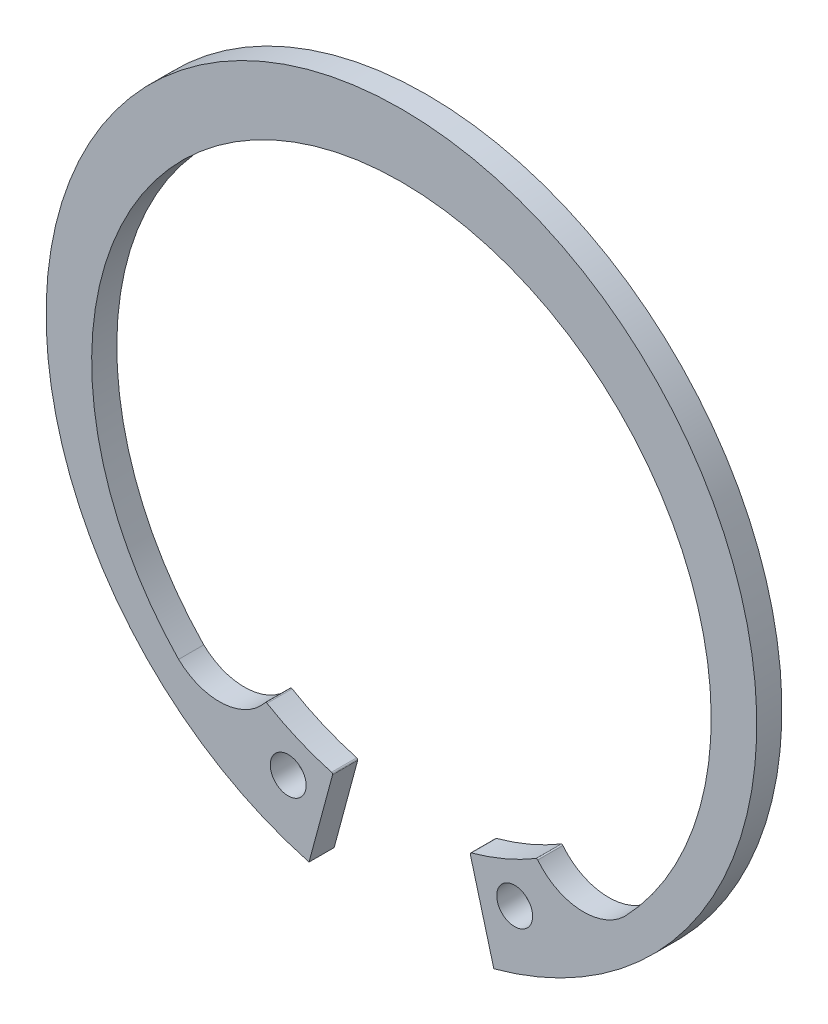
SolidWorks part; units mm, degrees
ref_plane "Plane1" through (0, 0, 0) normal (0, 0, 1) x (1, 0, 0)
ref_plane "Plane2" through (0, 0, 0) normal (0, 1, 0) x (1, 0, 0)
ref_plane "Plane3" through (0, 0, 0) normal (1, 0, 0) x (0, 0, -1)
sketch "Clipboard" plane through (0, 0, 0) normal (0, 0, 1) x (1, 0, 0)
  line L0 (0, 0) -> (4.4, 0)
  line L1 (0, 0) -> (0, 2.2)
  line L2 (0, 0) -> (0, -6.4)
  circle A0 centre (0, 0) radius 1.25
  circle A1 centre (0, 0) radius 23.5
  dimension "HoleDia" = 2.5
  dimension "BoreDia" = 47
  dimension "LargeSection" = 4.4
  dimension "SmallSection" = 2.2
  dimension "LugSection" = 6.4
sketch "BodySke" plane through (0, 0, 0) normal (0, 0, 1) x (1, 0, 0)
  line L0 (-1.5431, 0) -> (1.5431, 0) construction
  line L1 (0, 0) -> (0, 20.35) construction
  line L2 (6.4361, -23.8985) -> (5.4001, -20.0515)
  line L3 (-6.4361, -23.8985) -> (-5.4001, -20.0515)
  line L4 (0, 0) -> (14.6742, -19.9307) construction
  line L5 (0, 0) -> (-14.6742, -19.9307) construction
  line L6 (-7.5614, -18.1749) -> (-8.2115, -20.5889) construction
  line L7 (7.6913, -18.6572) -> (8.0817, -20.1067) construction
  arc A0 (-5.4001, -20.0515) -> (-9.8643, -17.733) centre (-7.8865, -19.3819) ccw
  arc A1 (9.8643, -17.733) -> (5.4001, -20.0515) centre (7.8865, -19.3819) ccw
  arc A2 (13.3698, -18.159) -> (-13.3698, -18.159) centre (0, -1.2254) ccw construction
  arc A3 (6.4361, -23.8985) -> (-6.4361, -23.8985) centre (0, 0) ccw
  circle A4 centre (7.8865, -19.3819) radius 1.25
  circle A5 centre (-7.8865, -19.3819) radius 1.25
  circle A6 centre (7.8865, -19.3819) radius 2.575 construction
  arc A7 (13.447, -18.0978) -> (-13.447, -18.0978) centre (0, -1.2254) ccw
  arc A8 (-7.8865, -19.3819) -> (7.8865, -19.3819) centre (0, 0) ccw construction
  arc A9 (-13.447, -18.0978) -> (-9.8643, -17.733) centre (-11.8421, -16.0841) ccw
  arc A10 (9.8643, -17.733) -> (13.447, -18.0978) centre (11.8421, -16.0841) ccw
  dimension "HoleDia" = 2.5
  dimension "HoleOffsetRad" = 20.925
  dimension "GrooveDia" = 49.5
  dimension "TipRad" = 2.575
  dimension "FilletRad" = 2.575
  dimension "LargeRad" = 20.35
  dimension "SmallRad" = 22.55
  dimension "SmallAngle" = 72.726
  dimension "GapAngle" = 30.145
extrude "Body" add sketch "BodySke" against normal blind 1.75
sketch "ModLugSke" plane through (0, 0, 0) normal (0, 0, 1) x (1, 0, 0)
  line L0 (6.4361, -23.8985) -> (4.7978, -17.815)
  line L1 (-6.4361, -23.8985) -> (-4.7978, -17.815)
  line L2 (12.689, -13.2556) -> (17.1146, -17.8788) construction
  line L3 (-12.689, -13.2556) -> (-17.1146, -17.8788) construction
  line L4 (-6.4361, -23.8985) -> (-5.4001, -20.0515) construction
  line L5 (5.4001, -20.0515) -> (6.4361, -23.8985) construction
  line L6 (0, 0) -> (0, -18.0732) construction
  line L7 (15.5173, -16.2102) -> (17.1146, -17.8788)
  line L8 (-17.1146, -17.8788) -> (-15.5173, -16.2102)
  arc A0 (6.4361, -23.8985) -> (17.1146, -17.8788) centre (0, 0) ccw
  arc A1 (-9.362, -15.7821) -> (-4.8678, -17.6926) centre (0, 0) ccw
  arc A2 (6.4361, -23.8985) -> (-6.4361, -23.8985) centre (0, 0) ccw construction
  arc A3 (9.8643, -17.733) -> (5.4001, -20.0515) centre (7.8865, -19.3819) ccw construction
  arc A4 (-9.362, -15.7821) -> (-9.4912, -15.8058) centre (-9.4131, -15.8681) ccw
  arc A5 (-15.5173, -16.2102) -> (-9.4912, -15.8058) centre (-12.689, -13.2556) ccw
  arc A6 (13.447, -18.0978) -> (-13.447, -18.0978) centre (0, -1.2254) ccw construction
  arc A7 (9.4912, -15.8058) -> (15.5173, -16.2102) centre (12.689, -13.2556) ccw
  arc A8 (4.8678, -17.6926) -> (9.362, -15.7821) centre (0, 0) ccw
  arc A9 (-17.1146, -17.8788) -> (-6.4361, -23.8985) centre (0, 0) ccw
  circle A10 centre (-7.8865, -19.3819) radius 1.25
  circle A11 centre (-7.8865, -19.3819) radius 1.25 construction
  circle A12 centre (7.8865, -19.3819) radius 1.25
  circle A13 centre (7.8865, -19.3819) radius 1.25 construction
  arc A14 (-4.8678, -17.6926) -> (-4.7978, -17.815) centre (-4.8943, -17.789) cw
  arc A15 (4.8678, -17.6926) -> (4.7978, -17.815) centre (4.8943, -17.789) ccw
  arc A16 (9.362, -15.7821) -> (9.4912, -15.8058) centre (9.4131, -15.8681) cw
  point P43 (4.7718, -17.7187)
  dimension "D1" = 0.1
  dimension "LugAng" = 61.353
extrude "ModLug" add sketch "ModLugSke" against normal through all
sketch "UnlSke" [suppressed] plane through (0, 0, 0) normal (0, 0, 1) x (1, 0, 0)
  line L0 (2.1178, -8.3352) -> (3.2259, -12.6966)
  line L1 (-2.1178, -8.3352) -> (-3.2259, -12.6966)
  line L2 (-3.2259, -12.6966) -> (-2.1422, -8.4315) construction
  line L3 (2.1422, -8.4315) -> (3.2259, -12.6966) construction
  arc A0 (2.1178, -8.3352) -> (-2.1178, -8.3352) centre (0, 0) ccw
  arc A1 (3.2259, -12.6966) -> (-3.2259, -12.6966) centre (0, 0) ccw
  arc A2 (3.2259, -12.6966) -> (-3.2259, -12.6966) centre (0, 0) ccw construction
  circle A4 centre (-4.4431, -9.5688) radius 1
  circle A5 centre (4.4431, -9.5688) radius 1
  circle A6 centre (4.4431, -9.5688) radius 1 construction
  circle A7 centre (-4.4431, -9.5688) radius 1 construction
  arc A8 (2.2134, -8.3103) -> (4.9183, -7.0548) centre (0, 0) ccw construction
extrude "Unlug" [suppressed] add sketch "UnlSke" against normal through all
equation "' \"BoreDia@Clipboard\" = 8"
equation "' \"Thickness@Body\" = 0.8"
equation "' \"GrooveDia@BodySke\" = 8.4"
equation "' \"LugSection@Clipboard\" = 2.4"
equation "' \"LargeSection@Clipboard\" = 1.1"
equation "' \"HoleDia@Clipboard\" = 1.0"
equation "' \"BoreDia@Clipboard\" = 25"
equation "' \"Thickness@Body\" = 1.2"
equation "' \"GrooveDia@BodySke\" = 26.2"
equation "' \"LugSection@Clipboard\" = 4.5"
equation "' \"LargeSection@Clipboard\" = 2.7"
equation "' \"HoleDia@Clipboard\" = 2"
equation "\"SmallSection@Clipboard\" = \"LargeSection@Clipboard\" * 0.5"
equation "\"TipRad@BodySke\" = (\"LugSection@Clipboard\" - (\"GrooveDia@BodySke\" / 2  -  \"BoreDia@Clipboard\" / 2 ) ) / 2"
equation "\"HoleOffsetRad@BodySke\" = (\"GrooveDia@BodySke\" / 2) - \"LugSection@Clipboard\"  + \"TipRad@BodySke\""
equation "\"LargeRad@BodySke\" =  \"GrooveDia@BodySke\" / 2 -  \"LargeSection@Clipboard\""
equation "\"SmallRad@BodySke\" =  \"GrooveDia@BodySke\" / 2 -  \"SmallSection@Clipboard\""
equation "\"HoleDia@BodySke\" =  \"HoleDia@Clipboard\""
equation "\"FilletRad@BodySke\" = \"TipRad@BodySke\" * 1.0"
equation "\"GapAngle@BodySke\" = 360 - 0.965 * 360 * ( \"BoreDia@Clipboard\" /  \"GrooveDia@BodySke\")"
equation "\"LugAng@ModLugSke\" = \"GapAngle@BodySke\"  + 2 * 360 * (\"LugSection@Clipboard\" / (\"BoreDia@Clipboard\" * 3.1416))"
